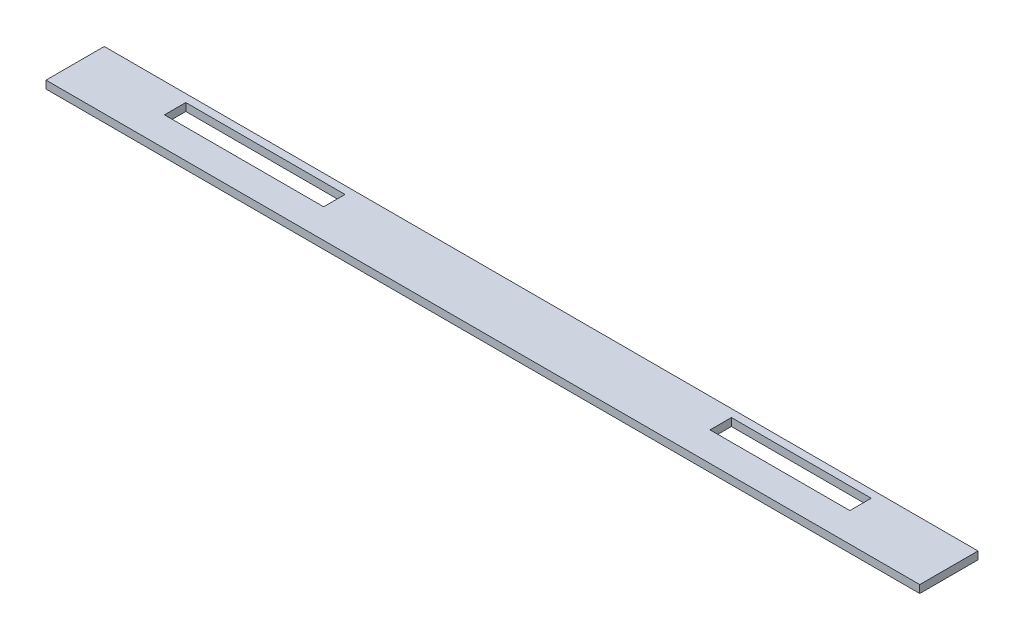
SolidWorks part; units mm, degrees
ref_plane "前基準面" through (0, 0, 0) normal (0, 0, 1) x (1, 0, 0)
ref_plane "上基準面" through (0, 0, 0) normal (0, 1, 0) x (1, 0, 0)
ref_plane "右基準面" through (0, 0, 0) normal (1, 0, 0) x (0, 0, -1)
sketch "草圖1" plane through (0, 0, 0) normal (0, 1, 0) x (1, 0, 0)
  line L0 (0, 0) -> (450, 0)
  line L1 (450, 0) -> (450, 30)
  line L2 (450, 30) -> (0, 30)
  line L3 (0, 30) -> (0, 0)
  dimension "D1" = 30
  dimension "D2" = 450
extrude "填料-伸長1" add sketch "草圖1" along normal blind 4
sketch "草圖2" plane through (0, 4, 0) normal (0, 1, 0) x (1, 0, 0)
  line L0 (47, 25) -> (47, 16)
  line L1 (47, 16) -> (127, 16)
  line L2 (127, 16) -> (127, 25)
  line L3 (127, 25) -> (47, 25)
  line L4 (0, 30) -> (0, 0) construction
  line L5 (128, 26) -> (46, 26)
  line L6 (328, 25) -> (328, 16)
  line L7 (328, 16) -> (398, 16)
  line L8 (398, 16) -> (398, 25)
  line L9 (398, 25) -> (328, 25)
  line L10 (450, 0) -> (450, 30) construction
  line L11 (450, 30) -> (0, 30) construction
  line L12 (46, 26) -> (46, 15)
  line L13 (46, 15) -> (128, 15)
  line L14 (128, 15) -> (128, 26)
  line L15 (399, 26) -> (327, 26)
  line L16 (327, 26) -> (327, 15)
  line L17 (327, 15) -> (399, 15)
  line L18 (399, 15) -> (399, 26)
  dimension "D1" = 9
  dimension "D2" = 80
  dimension "D3" = 47
  dimension "D4" = 5
  dimension "D5" = 70
  dimension "D6" = 9
  dimension "D7" = 52
  dimension "D8" = 5
  dimension "D9" = 1
  dimension "D10" = 1
extrude "除料-伸長1" cut sketch "草圖2" against normal through all contours L17 L18 L15 L16 | L13 L14 L5 L12
